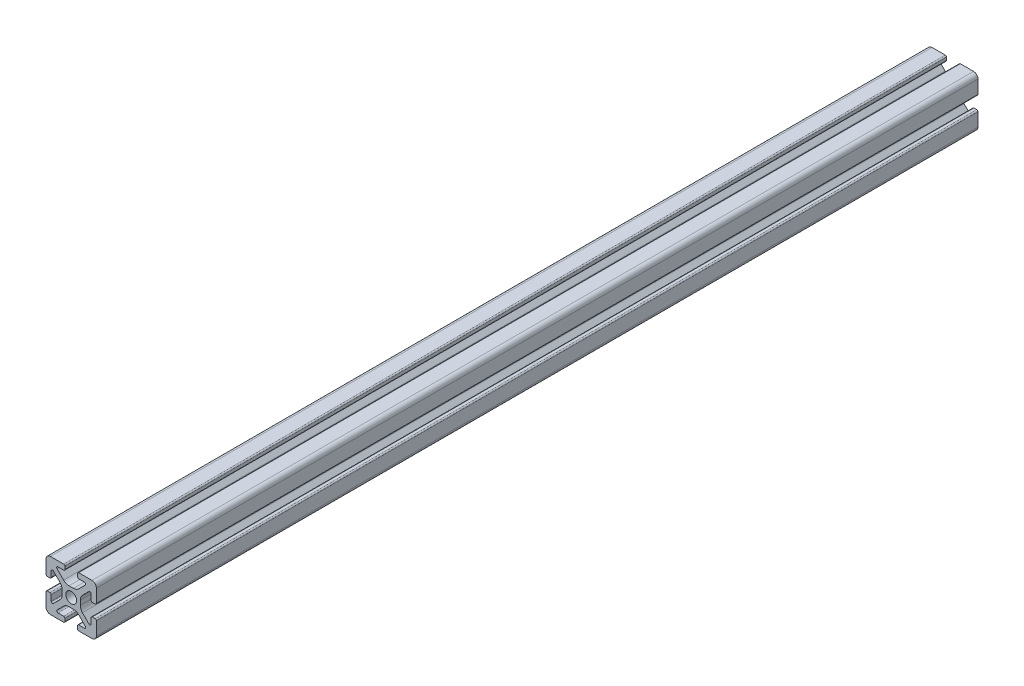
SolidWorks part; units mm, degrees
material "6063-T6"
ref_plane "Front Plane" through (0, 0, 0) normal (0, 0, 1) x (1, 0, 0)
ref_plane "Top Plane" through (0, 0, 0) normal (0, 1, 0) x (1, 0, 0)
ref_plane "Right Plane" through (0, 0, 0) normal (1, 0, 0) x (0, 0, -1)
sketch "Sketch2" plane through (0, 0, 0) normal (0, 0, 1) x (1, 0, 0)
  line L0 (0, 10) -> (0, -10) construction
  line L1 (-10, 0) -> (10, 0) construction
  line L2 (2.5, -10) -> (10, -10)
  line L3 (10, -10) -> (10, -2.5)
  line L4 (2.5, -10) -> (2.5, -7.9246)
  line L5 (2.5, -7.9246) -> (6.4571, -7.9246)
  line L6 (6.4571, -7.9246) -> (2.1325, -3.6)
  line L7 (0, 0) -> (10, -10) construction
  line L8 (10, -2.5) -> (7.9246, -2.5)
  line L9 (7.9246, -2.5) -> (7.9246, -6.4571)
  line L10 (7.9246, -6.4571) -> (3.6, -2.1325)
  line L11 (5.7623, -4.2948) -> (4.2948, -5.7623) construction
  circle A0 centre (0, 0) radius 2.15
  arc A1 (5.25, -7.9246) -> (5.6036, -7.0711) centre (5.25, -7.4246) ccw construction
  point P8 (0, -3.6)
  point P16 (5.0286, -5.0286)
  dimension "Center Hole Diameter" = 4.3
  dimension "D3" = 0.5
  dimension "Rail Height" = 20
  dimension "Rail Width" = 20
  dimension "T-Slot Width" = 5
  dimension "Slot Depth" = 6.4
  dimension "Slot Inner Width" = 11.5
sketch "Sketch3" plane through (0, 0, 0) normal (1, 0, 0) x (0, 0, -1)
  line L0 (-175, -10) -> (175, -10) construction
  line L1 (-149.6, 0) -> (149.6, 0) construction
  line L2 (0, 10) -> (0, -10) construction
  line L3 (0, 10) -> (0, -10) construction
  point P6 (-149.6, 0)
  point P8 (149.6, 0)
  dimension "Length" = 350
  dimension "D1" = 25.4
sketch "Sketch4" plane through (0, 0, 0) normal (0, 0, 1) x (1, 0, 0)
  line L0 (3, -10) -> (8.25, -10)
  line L1 (2.5, -10) -> (10, -10) construction
  line L2 (2.5, -10) -> (2.5, -7.9246) construction
  line L3 (2.5, -7.9246) -> (6.4571, -7.9246) construction
  line L4 (2.5, -8.4246) -> (2.5, -9.5)
  line L5 (3, -7.9246) -> (5.25, -7.9246)
  line L6 (0, -3.6) -> (0.8898, -3.6)
  line L7 (6.4571, -7.9246) -> (2.1325, -3.6) construction
  line L8 (3.0112, -4.4787) -> (5.6036, -7.0711)
  line L9 (10, -10) -> (10, -2.5) construction
  line L10 (7.9246, -6.4571) -> (3.6, -2.1325) construction
  line L11 (7.9246, -2.5) -> (7.9246, -6.4571) construction
  line L12 (7.9246, -5.25) -> (7.9246, -3)
  line L13 (10, -2.5) -> (7.9246, -2.5) construction
  line L14 (8.4246, -2.5) -> (9.5, -2.5)
  line L15 (10, -3) -> (10, -8.25)
  line L16 (7.0711, -5.6036) -> (4.4787, -3.0112)
  line L17 (3.6, 0) -> (3.6, -0.8898)
  line L18 (-10, 0) -> (10, 0) construction
  line L19 (0, -3.6) -> (0, -2.15)
  line L20 (0, 10) -> (0, -10) construction
  line L21 (3.6, 0) -> (2.15, 0)
  arc A0 (2.5, -9.5) -> (3, -10) centre (3, -9.5) ccw
  arc A1 (5.25, -7.9246) -> (5.6036, -7.0711) centre (5.25, -7.4246) ccw construction
  arc A2 (2.5, -8.4246) -> (3, -7.9246) centre (3, -8.4246) cw
  arc A3 (5.25, -7.9246) -> (5.6036, -7.0711) centre (5.25, -7.4246) ccw
  arc A4 (0.8898, -3.6) -> (3.0112, -4.4787) centre (0.8898, -6.6) cw
  arc A5 (8.25, -10) -> (10, -8.25) centre (8.25, -8.25) ccw
  arc A6 (7.0711, -5.6036) -> (7.9246, -5.25) centre (7.4246, -5.25) ccw
  arc A7 (7.9246, -3) -> (8.4246, -2.5) centre (8.4246, -3) cw
  arc A8 (9.5, -2.5) -> (10, -3) centre (9.5, -3) cw
  arc A9 (4.4787, -3.0112) -> (3.6, -0.8898) centre (6.6, -0.8898) cw
  circle A10 centre (0, 0) radius 2.15 construction
  arc A11 (0, -2.15) -> (2.15, 0) centre (0, 0) ccw
  dimension "D1" = 1.75
  dimension "D2" = 3
extrude "Boss-Extrude1" add sketch "Sketch4" along normal mid plane 350
mirror "Mirror1" about plane through (0, 0, 0) normal (1, 0, 0) of bodies 134
mirror "Mirror2" about plane through (0, 0, 0) normal (0, 1, 0) of bodies 135
equation "\"D3@Sketch2\"=\"T-Slot Width@Sketch2\"*0.1"
equation "\"D1@Sketch4\"=\"D3@Sketch2\"*3.5"
equation "\"D2@Sketch4\"=\"D3@Sketch2\"*6"
equation "\"D1@Boss-Extrude1\"=\"Length@Sketch3\""
